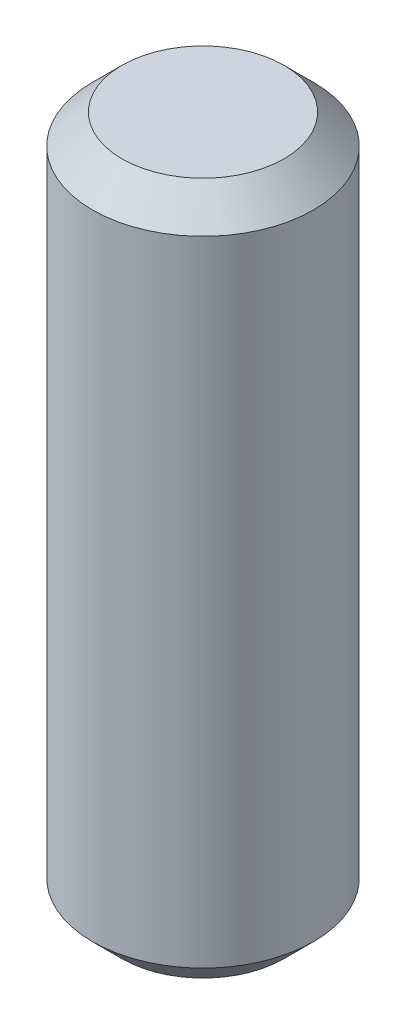
SolidWorks part; units mm, degrees
ref_plane "Front Plane" through (0, 0, 0) normal (0, 0, 1) x (1, 0, 0)
ref_plane "Top Plane" through (0, 0, 0) normal (0, 1, 0) x (1, 0, 0)
ref_plane "Right Plane" through (0, 0, 0) normal (1, 0, 0) x (0, 0, -1)
sketch "Sketch1" plane through (0, 0, 0) normal (0, 1, 0) x (1, 0, 0)
  circle A0 centre (0, 0) radius 0.75
  dimension "D1" = 1.5
extrude "Boss-Extrude1" add sketch "Sketch1" along normal blind 4.7
chamfer "Chamfer1" distance 0.2 angle 45 2 edges at (0, 0, 0.75) (0, 4.7, 0.75)
